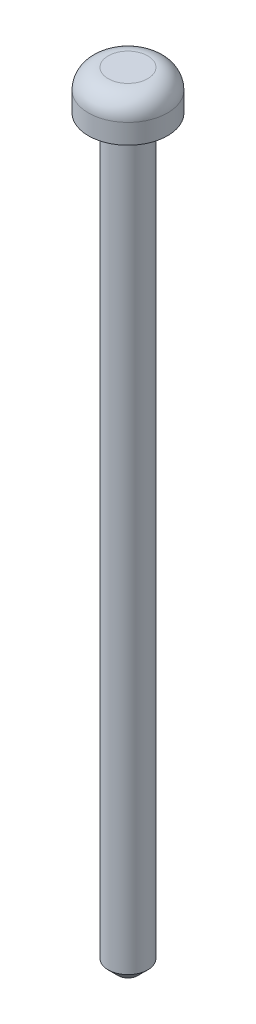
SolidWorks part; units mm, degrees
ref_plane "Front Plane" through (0, 0, 0) normal (0, 0, 1) x (1, 0, 0)
ref_plane "Top Plane" through (0, 0, 0) normal (0, 1, 0) x (1, 0, 0)
ref_plane "Right Plane" through (0, 0, 0) normal (1, 0, 0) x (0, 0, -1)
sketch "Sketch1" plane through (0, 0, 0) normal (0, 1, 0) x (1, 0, 0)
  circle A0 centre (0, 0) radius 2.032
  dimension "D1" = 4.064
extrude "Boss-Extrude1" add sketch "Sketch1" along normal blind 76.2
sketch "Sketch2" plane through (0, 76.2, 0) normal (0, 1, 0) x (1, 0, 0)
  circle A0 centre (0, 0) radius 4.064
  dimension "D1" = 8.128
extrude "Boss-Extrude2" add sketch "Sketch2" along normal blind 4.064
fillet "Fillet1" radius 2.032 1 edges at (0, 80.264, 4.064)
chamfer "Chamfer1" distance 1.016 angle 45 1 edges at (0, 0, 2.032)
